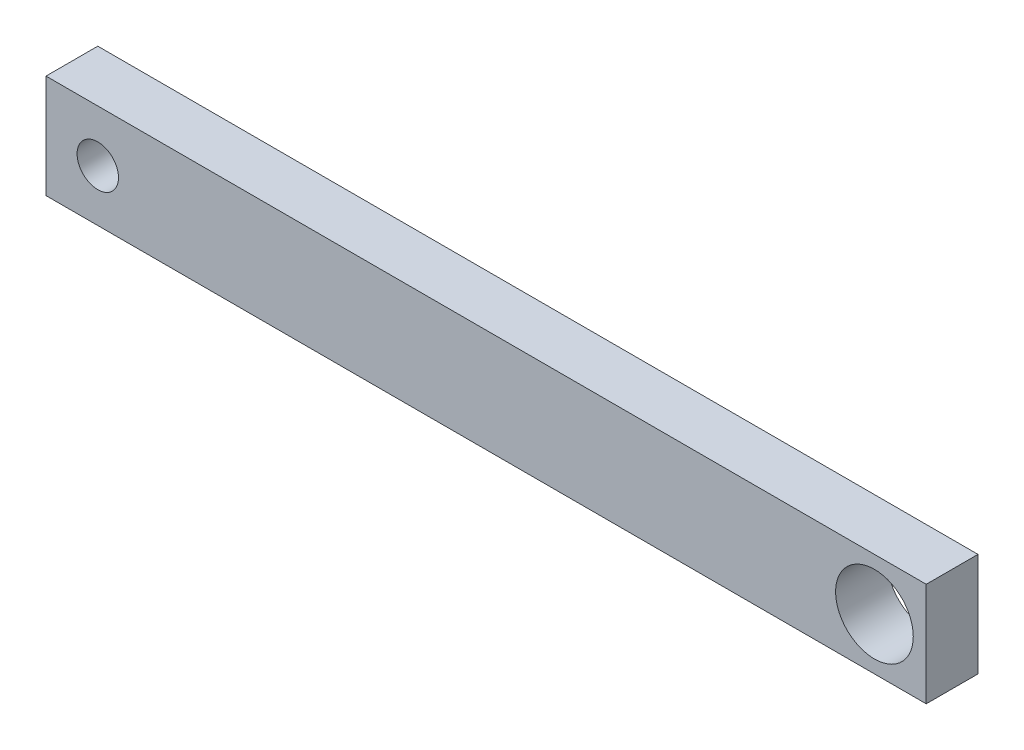
SolidWorks part; units mm, degrees
ref_plane "前视基准面" through (0, 0, 0) normal (0, 0, 1) x (1, 0, 0)
ref_plane "上视基准面" through (0, 0, 0) normal (0, 1, 0) x (1, 0, 0)
ref_plane "右视基准面" through (0, 0, 0) normal (1, 0, 0) x (0, 0, -1)
sketch "草图1" plane through (0, 0, 0) normal (0, 0, 1) x (1, 0, 0)
  line L0 (85, 0) -> (85, -33.2685) construction
  line L1 (0, 0) -> (170, 0)
  line L2 (0, 0) -> (0, -20)
  line L3 (0, -20) -> (170, -20)
  line L4 (170, 0) -> (170, -20)
  line L5 (0, -10) -> (10, -10) construction
  circle A0 centre (10, -10) radius 4
  circle A1 centre (160, -10) radius 4 construction
  circle A2 centre (160, -10) radius 7.5
  dimension "D3" = 8
  dimension "D4" = 150
  dimension "D5" = 15
  dimension "D1" = 170
  dimension "D2" = 20
extrude "凸台-拉伸1" add sketch "草图1" along normal blind 10
